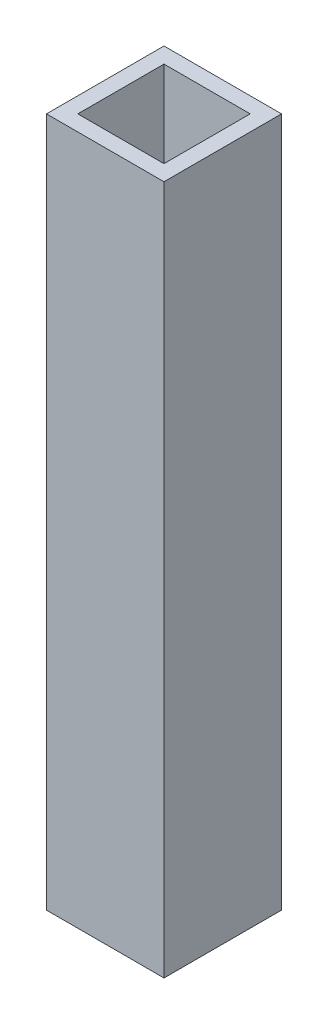
SolidWorks part; units mm, degrees
ref_plane "Front Plane" through (0, 0, 0) normal (0, 0, 1) x (1, 0, 0)
ref_plane "Top Plane" through (0, 0, 0) normal (0, 1, 0) x (1, 0, 0)
ref_plane "Right Plane" through (0, 0, 0) normal (1, 0, 0) x (0, 0, -1)
sketch "Sketch1" plane through (0, 0, 0) normal (0, 1, 0) x (1, 0, 0)
  line L0 (2, 2) -> (2, 13)
  line L1 (0, 0) -> (15, 0)
  line L2 (0, 0) -> (0, 15)
  line L3 (0, 15) -> (15, 15)
  line L4 (15, 0) -> (15, 15)
  line L5 (2, 13) -> (13, 13)
  line L6 (13, 2) -> (13, 13)
  line L7 (2, 2) -> (13, 2)
  dimension "D1" = 15
  dimension "D2" = 2
extrude "Boss-Extrude1" add sketch "Sketch1" along normal blind 88
